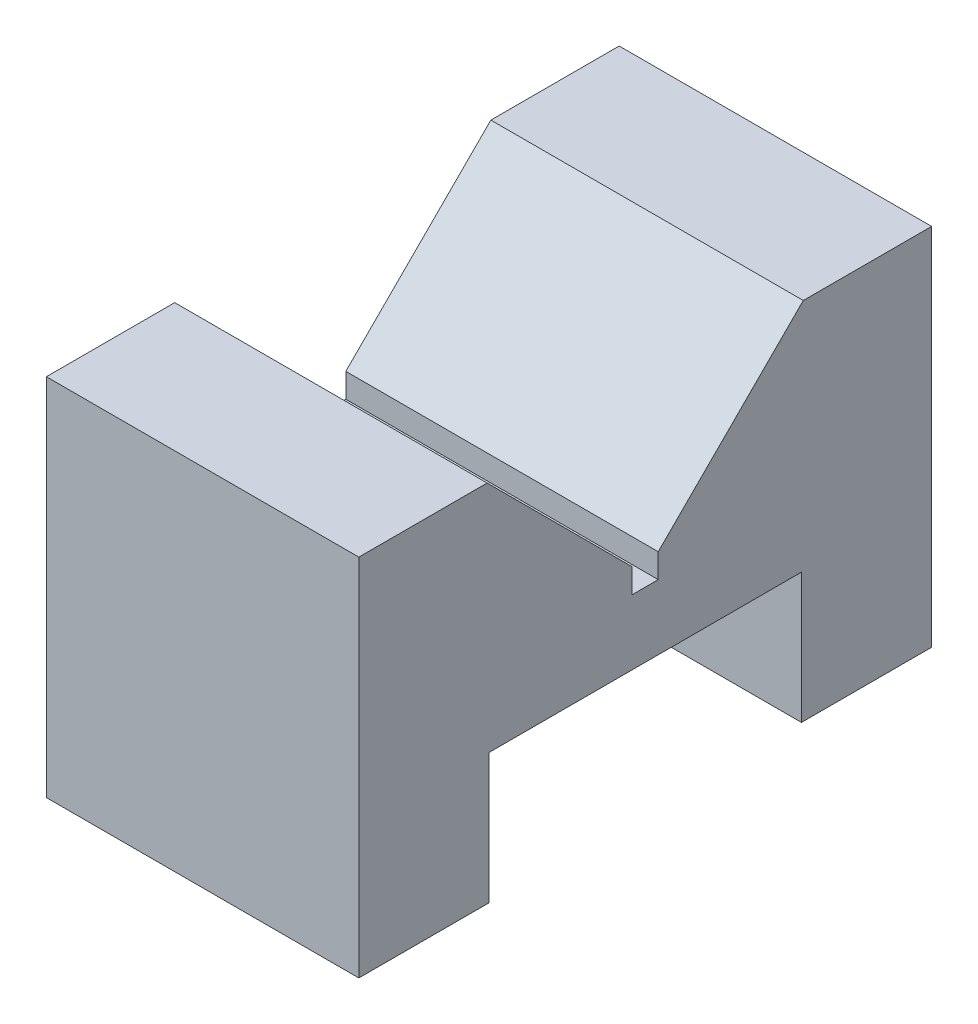
SolidWorks part; units mm, degrees
material "AISI 1020"
ref_plane "Front Plane" through (0, 0, 0) normal (0, 0, 1) x (1, 0, 0)
ref_plane "Top Plane" through (0, 0, 0) normal (0, 1, 0) x (1, 0, 0)
ref_plane "Right Plane" through (0, 0, 0) normal (1, 0, 0) x (0, 0, -1)
sketch "Sketch1" plane through (0, 0, 0) normal (1, 0, 0) x (0, 0, -1)
  line L0 (0, 0) -> (0, 31.3939) construction
  line L1 (12, 10) -> (-12, 10)
  line L2 (-12, 10) -> (-12, 0)
  line L3 (-12, 0) -> (-22, 0)
  line L4 (-22, 0) -> (-22, 28)
  line L5 (-22, 28) -> (-12.1421, 28)
  line L6 (-12.1421, 28) -> (-1, 16.8579)
  line L7 (-1, 16.8579) -> (-1, 15)
  line L8 (-1, 15) -> (1, 15)
  line L9 (1, 16.8579) -> (1, 15)
  line L10 (12.1421, 28) -> (1, 16.8579)
  line L11 (22, 28) -> (12.1421, 28)
  line L12 (22, 0) -> (22, 28)
  line L13 (12, 0) -> (22, 0)
  line L14 (12, 10) -> (12, 0)
  circle A0 centre (0, 30) radius 10 construction
  point P13 (0, 15)
  point P19 (0, 10)
  point P21 (1, 15.9289)
  dimension "D6" = 20
  dimension "D1" = 44
  dimension "D2" = 24
  dimension "D3" = 10
  dimension "D4" = 28
  dimension "D5" = 90
  dimension "D7" = 13
  dimension "D8" = 40
  dimension "D9" = 2
extrude "Boss-Extrude1" add sketch "Sketch1" along normal blind 24
hole_wizard "M5 Tapped Hole1" positions "Sketch2" profile "Sketch3" tap size "M5" standard "ISO"
sketch "Sketch2" plane through (0, 0, 0) normal (0, -1, 0) x (-1, 0, 0)
  line L0 (0, 0) -> (-29.0373, 0) construction
  line L2 (0, -12) -> (0, 12) construction
  point P0 (-13, 17)
  point P2 (-13, -17)
  dimension "D1" = 13
  dimension "D2" = 34
sketch "Sketch3" plane through (13, 0, -17) normal (1, 0, 0) x (0, 0, -1)
  line L0 (0, 0) -> (0, 13.2618)
  line L1 (0, 13.2618) -> (2.1, 12)
  line L2 (2.1, 12) -> (2.1, 0)
  line L5 (2.1, 0) -> (0, 0)
  line L10 (0, 13.2618) -> (-2.1, 12) construction
  line L11 (0, -6.35) -> (0, 107.95) construction
  dimension "Tap Drill Dia." = 4.2
  dimension "Tap Drill Depth" = 12
  dimension "Drill Angle" = 118
cosmetic thread "Hole Thread1" parameters "D1"=9, "D2"=5
cosmetic thread "Hole Thread2" parameters "D1"=9, "D2"=5
